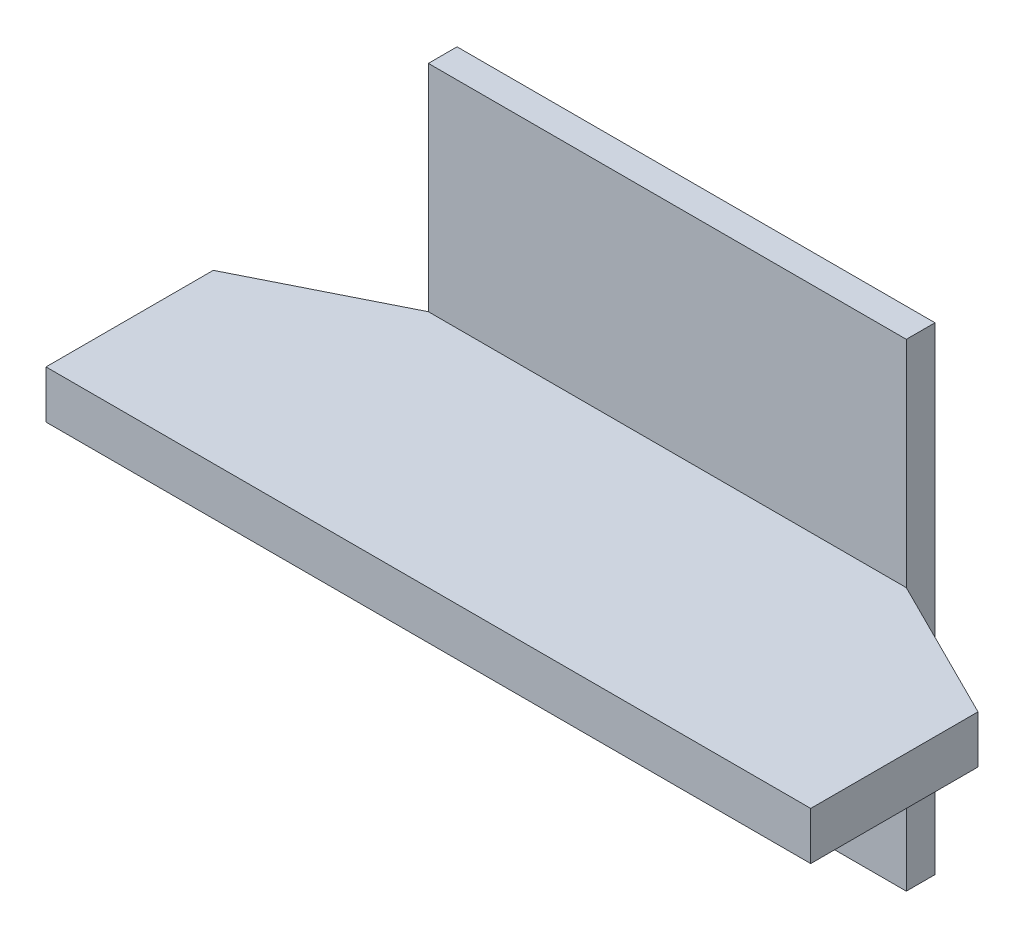
SolidWorks part; units mm, degrees
ref_plane "前视基准面" through (0, 0, 0) normal (0, 0, 1) x (1, 0, 0)
ref_plane "上视基准面" through (0, 0, 0) normal (0, 1, 0) x (1, 0, 0)
ref_plane "右视基准面" through (0, 0, 0) normal (1, 0, 0) x (0, 0, -1)
sketch "草图1" plane through (0, 0, 0) normal (0, 0, 1) x (1, 0, 0)
  line L1 (0, 0) -> (200, 0)
  line L2 (0, 0) -> (0, 200)
  line L3 (0, 200) -> (200, 200)
  line L4 (200, 0) -> (200, 200)
  dimension "D1" = 200
  dimension "D2" = 200
extrude "拉伸1" add sketch "草图1" along normal blind 12
sketch "草图3" plane through (0, 0, 12) normal (0, 0, 1) x (1, 0, 0)
  line L0 (0, 0) -> (200, 0) construction
  line L1 (-60, 110) -> (260, 110)
  line L2 (-60, 110) -> (-60, 90)
  line L3 (-60, 90) -> (260, 90)
  line L4 (260, 110) -> (260, 90)
  line L7 (0, 200) -> (0, 0) construction
  line L10 (200, 0) -> (200, 200) construction
  dimension "D1" = 20
  dimension "D2" = 60
  dimension "D3" = 60
  dimension "D4" = 90
extrude "拉伸3" add sketch "草图3" along normal blind 100
sketch "草图4" plane through (0, 90, 0) normal (0, -1, 0) x (1, 0, 0)
  line L0 (200, 12) -> (260, 42)
  line L1 (200, 12) -> (260, 12) construction
  line L2 (260, 112) -> (260, 12) construction
  line L3 (-60, 42) -> (0, 12)
  line L4 (-60, 112) -> (-60, 12) construction
  line L5 (260, 42) -> (260, 12)
  line L6 (260, 12) -> (200, 12)
  line L7 (-60, 42) -> (-60, 12)
  line L8 (-60, 12) -> (0, 12)
  dimension "D1" = 30
  dimension "D2" = 30
extrude "拉伸4" cut sketch "草图4" against normal through all
